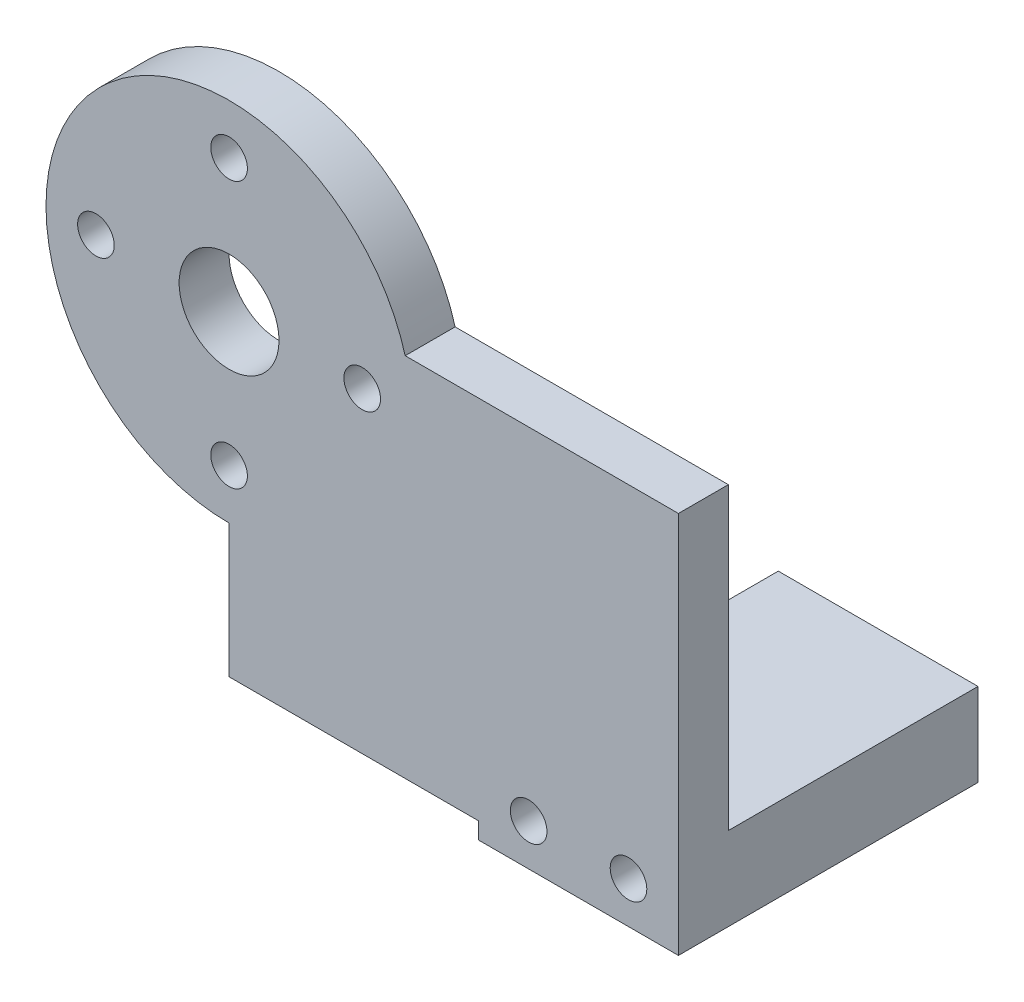
SolidWorks part; units mm, degrees
ref_plane "Front Plane" through (0, 0, 0) normal (0, 0, 1) x (1, 0, 0)
ref_plane "Top Plane" through (0, 0, 0) normal (0, 1, 0) x (1, 0, 0)
ref_plane "Right Plane" through (0, 0, 0) normal (1, 0, 0) x (0, 0, -1)
sketch "Stock_horn_attachment_profile" plane through (0, 0, 0) normal (0, 0, 1) x (1, 0, 0)
  circle A0 centre (0, 0) radius 11
  dimension "D1" = 22
extrude "Stock_horn_attachment" add sketch "Stock_horn_attachment_profile" along normal blind 3 from offset 15
sketch "Finger_arm_profile" plane through (0, 0, 0) normal (0, 0, 1) x (1, 0, 0)
  line L1 (0, -19) -> (27, -19)
  line L2 (0, -19) -> (0, 3)
  line L3 (0, 3) -> (27, 3)
  line L4 (27, -19) -> (27, 3)
  dimension "D1" = 27
  dimension "D2" = 22
  dimension "D3" = 3
extrude "Finger_arm" add sketch "Finger_arm_profile" along normal blind 3 from offset 15
sketch "Descending_contact_finger_profile" plane through (0, 0, 0) normal (0, 0, 1) x (1, 0, 0)
  line L1 (15, -20) -> (27, -20)
  line L2 (15, -20) -> (15, -15)
  line L3 (15, -15) -> (27, -15)
  line L4 (27, -20) -> (27, -15)
  dimension "D1" = 12
  dimension "D2" = 5
  dimension "D3" = 15
  dimension "D4" = 15
extrude "Descending_contact_finger" add sketch "Descending_contact_finger_profile" along normal blind 18
sketch "Horn_center_access_profile" plane through (0, 0, 0) normal (0, 0, 1) x (1, 0, 0)
  circle A0 centre (0, 0) radius 3
  dimension "D1" = 6
extrude "Horn_center_access" cut sketch "Horn_center_access_profile" along normal through all from offset 50
sketch "Horn_screws_profile" plane through (0, 0, 0) normal (0, 0, 1) x (1, 0, 0)
  circle A0 centre (0, -8) radius 1.1
  circle A1 centre (0, 8) radius 1.1
  circle A2 centre (-8, 0) radius 1.1
  circle A3 centre (8, 0) radius 1.1
  dimension "D1" = 2.2
  dimension "D2" = 2.2
  dimension "D3" = 2.2
  dimension "D4" = 2.2
  dimension "D5" = 8
  dimension "D6" = 8
  dimension "D7" = 8
  dimension "D8" = 8
extrude "Horn_screws" cut sketch "Horn_screws_profile" along normal through all from offset 50
sketch "Contact_pad_keeper_profile" plane through (0, 0, 0) normal (0, 0, 1) x (1, 0, 0)
  circle A0 centre (18, -17.5) radius 1.1
  circle A1 centre (24, -17.5) radius 1.1
  dimension "D1" = 2.2
  dimension "D2" = 2.2
  dimension "D3" = 18
  dimension "D4" = 24
  dimension "D5" = 17.5
extrude "Contact_pad_keeper" cut sketch "Contact_pad_keeper_profile" along normal through all from offset 50
